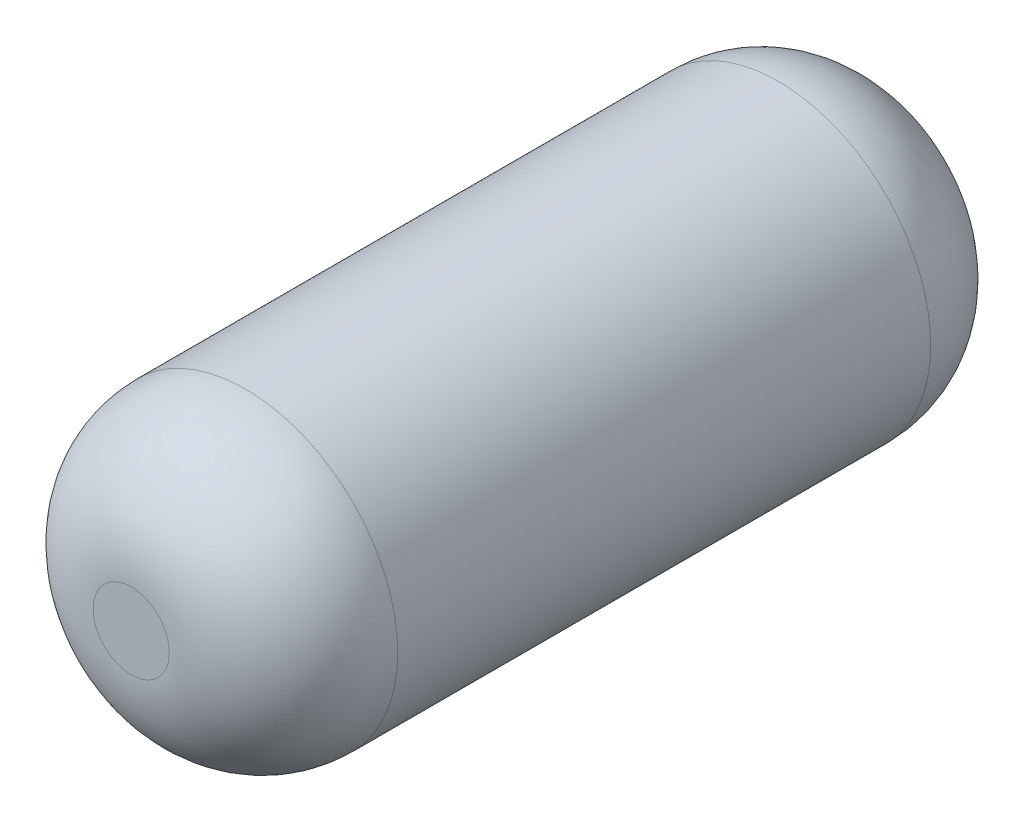
SolidWorks part; units mm, degrees
material "Acero al carbono fundido"
ref_plane "Front" through (0, 0, 0) normal (0, 0, 1) x (1, 0, 0)
ref_plane "Top" through (0, 0, 0) normal (0, 1, 0) x (1, 0, 0)
ref_plane "Right" through (0, 0, 0) normal (1, 0, 0) x (0, 0, -1)
sketch "Croquis1" plane through (0, 0, 0) normal (0, 0, 1) x (1, 0, 0)
  circle A0 centre (0, 0) radius 4
  dimension "D1" = 8
extrude "Saliente-Extruir1" add sketch "Croquis1" along normal blind 20
fillet "Redondeo1" radius 3 2 edges at (4, 0, 0) (4, 0, 20)
